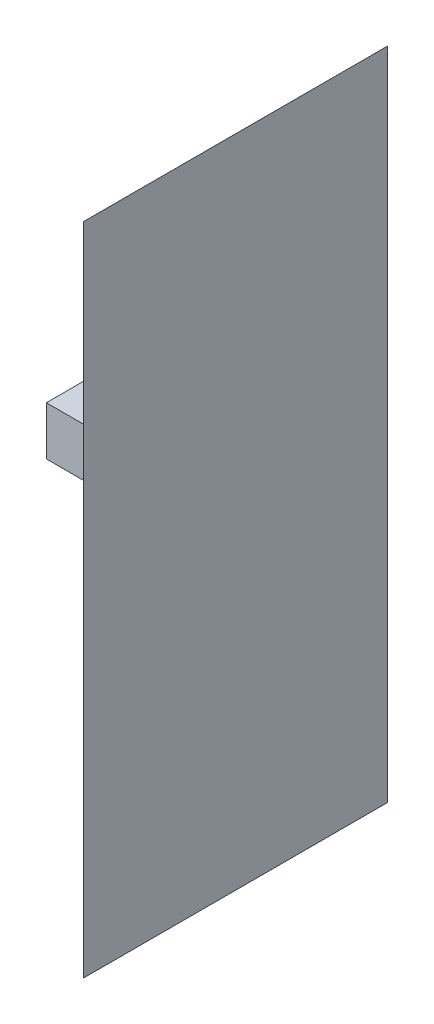
SolidWorks part; units mm, degrees
ref_plane "Front Plane" through (0, 0, 0) normal (1, 0, 0) x (0, 1, 0)
ref_plane "Top Plane" through (0, 0, 0) normal (0, 0, 1) x (0, 1, 0)
ref_plane "Right Plane" through (0, 0, 0) normal (0, 1, 0) x (-1, 0, 0)
sketch "Sketch1" plane through (0, 0, 0) normal (1, 0, 0) x (0, 1, 0)
  line L1 (7.0485, -7.0485) -> (-7.0485, -7.0485)
  line L2 (7.0485, -7.0485) -> (7.0485, 7.0485)
  line L3 (7.0485, 7.0485) -> (-7.0485, 7.0485)
  line L4 (-7.0485, -7.0485) -> (-7.0485, 7.0485)
  line L5 (7.0485, -7.0485) -> (-7.0485, 7.0485) construction
  line L6 (7.0485, 7.0485) -> (-7.0485, -7.0485) construction
  point P0 (0, 0)
  dimension "D1" = 14.097
extrude "Boss-Extrude1" add sketch "Sketch1" along normal blind 12.446
sketch "Sketch2" plane through (12.446, 0, 0) normal (1, 0, 0) x (0, 1, 0)
  circle A0 centre (0, 0) radius 5.08
  dimension "D1" = 10.16
extrude "Boss-Extrude2" add sketch "Sketch2" along normal blind 9.8806
sketch "Sketch3" plane through (0, 0, 0) normal (0, 1, 0) x (-1, 0, 0)
  circle A0 centre (-8.255, 0) radius 1
  dimension "D2" = 2
  dimension "D1" = 8.255
extrude "Cut-Extrude1" cut sketch "Sketch3" against normal through all both and the other way through all
sketch "Sketch4" plane through (0, 0, 0) normal (-1, 0, 0) x (0, -1, 0)
  line L0 (7.0485, 7.0485) -> (7.0485, -7.0485) construction
  line L1 (7.0485, -1.0795) -> (-3.2893, -1.0795)
  line L2 (7.0485, -1.0795) -> (7.0485, -4.5085)
  line L3 (7.0485, -4.5085) -> (-3.2893, -4.5085)
  line L4 (-3.2893, -1.0795) -> (-3.2893, -4.5085)
  line L5 (7.0485, -7.0485) -> (-7.0485, -7.0485) construction
  dimension "D1" = 3.429
  dimension "D2" = 10.3378
  dimension "D3" = 2.54
extrude "Boss-Extrude3" add sketch "Sketch4" along normal blind 3.429
sketch "Sketch5" plane through (22.3266, 0, 0) normal (1, 0, 0) x (0, 1, 0)
  point P0 (0, 0)
sketch "Sketch6" plane through (0, 0, 0) normal (0, 1, 0) x (-1, 0, 0)
  line L0 (-22.3266, 0) -> (-47.7266, 0) construction
  line L1 (-22.3266, 0) -> (-47.7266, 43.9941)
  line L2 (-22.3266, 0) -> (-47.7266, -43.9941)
  dimension "D1" = 120
  dimension "D2" = 25.4
sketch "Sketch7" plane through (0, 0, 0) normal (0, 0, 1) x (0, 1, 0)
  line L0 (0, -22.3266) -> (-94.7941, -47.7266)
  line L1 (0, -22.3266) -> (0, -47.7266) construction
  line L2 (0, -22.3266) -> (0, -47.7266) construction
  line L3 (0, -22.3266) -> (94.7941, -47.7266)
  dimension "D1" = 150
ref_plane "Plane1" through (47.7266, 0, 0) normal (1, 0, 0) x (0, 0, -1)
sketch "Sketch8" plane through (47.7266, 0, 0) normal (1, 0, 0) x (0, 0, -1)
  line L0 (0, 0) -> (0, 94.7941) construction
  line L1 (43.9941, -94.7941) -> (-43.9941, -94.7941)
  line L2 (43.9941, -94.7941) -> (43.9941, 94.7941)
  line L3 (43.9941, 94.7941) -> (-43.9941, 94.7941)
  line L4 (-43.9941, -94.7941) -> (-43.9941, 94.7941)
  line L5 (43.9941, -94.7941) -> (-43.9941, 94.7941) construction
  line L6 (43.9941, 94.7941) -> (-43.9941, -94.7941) construction
  line L7 (0, 0) -> (-43.9941, 0) construction
  line L8 (0, 0) -> (-43.9941, 0) construction
  line L9 (0, 0) -> (0, 94.7941) construction
  point P0 (0, 0)
loft "FOV" add profiles "Sketch8", "Sketch5"
